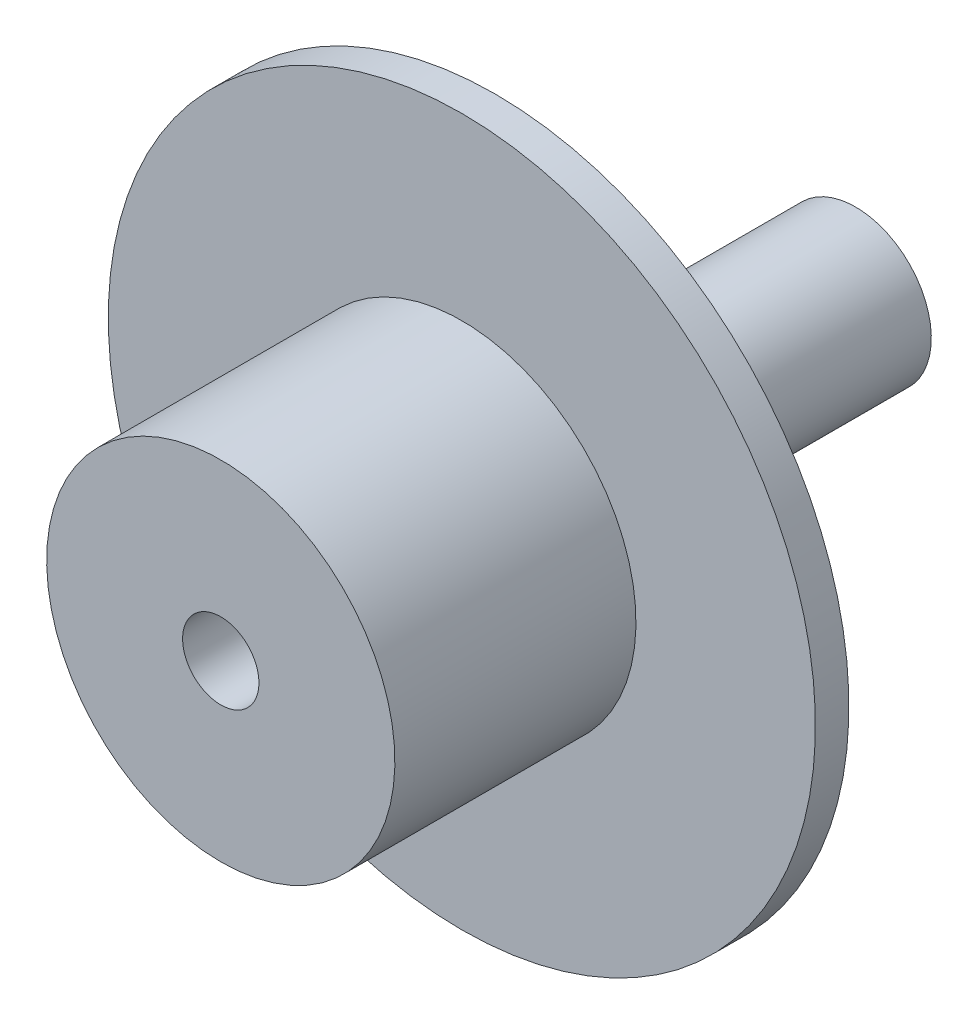
SolidWorks part; units mm, degrees
material "AISI 4340 Steel, normalized"
ref_plane "Front Plane" through (0, 0, 0) normal (0, 0, 1) x (1, 0, 0)
ref_plane "Top Plane" through (0, 0, 0) normal (0, 1, 0) x (1, 0, 0)
ref_plane "Right Plane" through (0, 0, 0) normal (1, 0, 0) x (0, 0, -1)
sketch "Sketch1" plane through (0, 0, 0) normal (1, 0, 0) x (0, 0, -1)
  line L0 (0, 0) -> (0, 130)
  line L3 (474, 0) -> (0, 0) construction
  line L4 (0, 0) -> (474, 0) construction
  line L5 (0, 130) -> (180, 130)
  line L6 (180, 130) -> (180, 264)
  line L7 (180, 264) -> (205, 264)
  line L8 (205, 264) -> (205, 56.5)
  line L9 (205, 56.5) -> (474, 56.5)
  line L10 (474, 56.5) -> (474, 0)
  line L11 (0, 0) -> (474, 0)
  dimension "D1" = 474
  dimension "D2" = 180
  dimension "D3" = 260
  dimension "D4" = 113
  dimension "D5" = 528
  dimension "D6" = 25
revolve "Revolve1" add sketch "Sketch1" angle 360 about L11
sketch "Sketch2" plane through (0, 0, 0) normal (0, 0, 1) x (1, 0, 0)
  circle A0 centre (0, 0) radius 28.5
  dimension "D1" = 57
extrude "Cut-Extrude1" cut sketch "Sketch2" against normal through all
